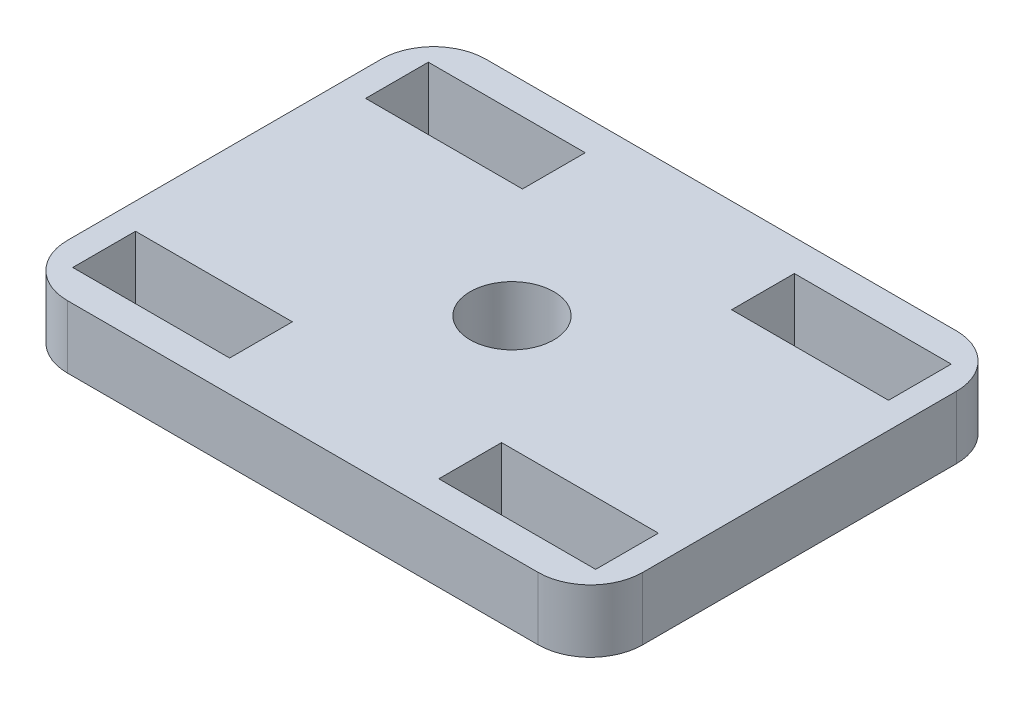
SolidWorks part; units mm, degrees
material "6061-T6 (SS)"
ref_plane "Alzado" through (0, 0, 0) normal (0, 0, 1) x (1, 0, 0)
ref_plane "Planta" through (0, 0, 0) normal (0, 1, 0) x (1, 0, 0)
ref_plane "Vista lateral" through (0, 0, 0) normal (1, 0, 0) x (0, 0, -1)
sketch "Croquis1" plane through (0, 0, 0) normal (0, 1, 0) x (1, 0, 0)
  line L1 (-27.5, -20) -> (27.5, -20)
  line L2 (-27.5, -20) -> (-27.5, 20)
  line L3 (-27.5, 20) -> (27.5, 20)
  line L4 (27.5, -20) -> (27.5, 20)
  line L5 (-27.5, -20) -> (27.5, 20) construction
  line L6 (-27.5, 20) -> (27.5, -20) construction
  point P0 (0, 0)
  dimension "D1" = 40
  dimension "D2" = 55
extrude "Saliente-Extruir1" add sketch "Croquis1" along normal mid plane 6
sketch "Croquis2" plane through (0, -3, 0) normal (0, -1, 0) x (-1, 0, 0)
  line L1 (25, -17) -> (10, -17)
  line L2 (25, -17) -> (25, -11)
  line L3 (25, -11) -> (10, -11)
  line L4 (10, -17) -> (10, -11)
  line L5 (-10, -17) -> (-25, -17)
  line L6 (-10, -17) -> (-10, -11)
  line L7 (-10, -11) -> (-25, -11)
  line L8 (-25, -17) -> (-25, -11)
  line L9 (25, 11) -> (10, 11)
  line L10 (25, 11) -> (25, 17)
  line L11 (25, 17) -> (10, 17)
  line L12 (10, 11) -> (10, 17)
  line L13 (-10, 11) -> (-25, 11)
  line L14 (-10, 11) -> (-10, 17)
  line L15 (-10, 17) -> (-25, 17)
  line L16 (-25, 11) -> (-25, 17)
extrude "Cortar-Extruir1" cut sketch "Croquis2" against normal through all
sketch "Croquis3" plane through (0, -3, 0) normal (0, -1, 0) x (-1, 0, 0)
  circle A0 centre (0, 0) radius 4
  dimension "D1" = 8
extrude "Cortar-Extruir2" cut sketch "Croquis3" against normal through all
fillet "Redondeo1" radius 5 4 edges at (27.5, 0, 20) (27.5, 0, -20) (-27.5, 0, -20) (-27.5, 0, 20)
